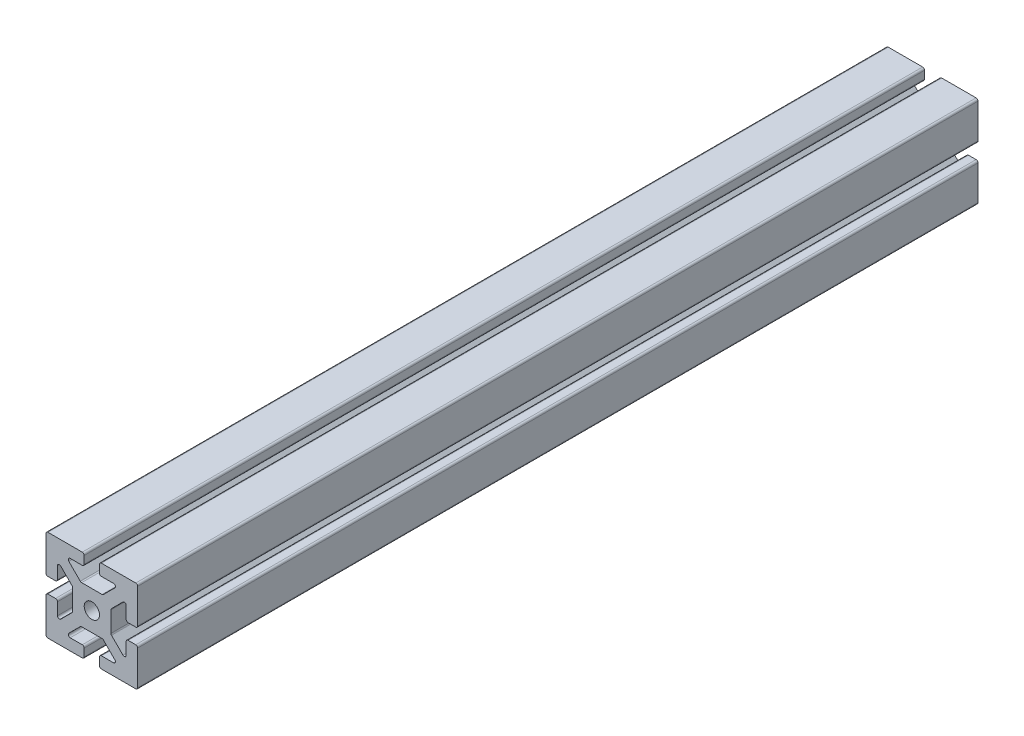
SolidWorks part; units mm, degrees
material "6061-T4 (SS)"
ref_plane "Front Plane" through (0, 0, 0) normal (0, 0, 1) x (1, 0, 0)
ref_plane "Top Plane" through (0, 0, 0) normal (0, 1, 0) x (1, 0, 0)
ref_plane "Right Plane" through (0, 0, 0) normal (1, 0, 0) x (0, 0, -1)
sketch "Sketch1" plane through (0, 0, 0) normal (0, 0, 1) x (1, 0, 0)
  line L0 (0, 0) -> (0, 6) construction
  line L5 (6, 6) -> (-6, 6) construction
  line L6 (6, 6) -> (6, -5.75) construction
  line L43 (5.75, -6) -> (-6, -6) construction
  line L45 (-6, 6) -> (-6, -6) construction
  line L49 (-1.3358, 2.5) -> (1.3358, 2.5)
  line L53 (1.5126, 2.5732) -> (3.0126, 4.0732)
  line L54 (2.8358, 4.5) -> (1.25, 4.5)
  line L55 (1, 4.75) -> (1, 5.75)
  line L56 (1.25, 6) -> (5.75, 6)
  line L60 (-1.5126, 2.5732) -> (-3.0126, 4.0732)
  line L61 (-2.8358, 4.5) -> (-1.25, 4.5)
  line L62 (-1, 4.75) -> (-1, 5.75)
  line L63 (-1.25, 6) -> (-5.75, 6)
  line L64 (6, 1.25) -> (6, 5.75)
  line L65 (4.75, 1) -> (5.75, 1)
  line L66 (4.5, 2.8358) -> (4.5, 1.25)
  line L68 (2.5732, 1.5126) -> (4.0732, 3.0126)
  line L86 (2.5, 1.3358) -> (2.5, -1.3358)
  line L87 (2.5732, -1.5126) -> (4.0732, -3.0126)
  line L88 (4.5, -2.8358) -> (4.5, -1.25)
  line L89 (4.75, -1) -> (5.75, -1)
  line L90 (6, -1.25) -> (6, -5.75)
  line L91 (1.25, -6) -> (5.75, -6)
  line L92 (1, -4.75) -> (1, -5.75)
  line L93 (2.8358, -4.5) -> (1.25, -4.5)
  line L94 (1.5126, -2.5732) -> (3.0126, -4.0732)
  line L95 (1.3358, -2.5) -> (-1.3358, -2.5)
  line L96 (-1.5126, -2.5732) -> (-3.0126, -4.0732)
  line L97 (-2.8358, -4.5) -> (-1.25, -4.5)
  line L98 (-1, -4.75) -> (-1, -5.75)
  line L99 (-1.25, -6) -> (-5.75, -6)
  line L100 (-6, -1.25) -> (-6, -5.75)
  line L101 (-4.75, -1) -> (-5.75, -1)
  line L102 (-4.5, -2.8358) -> (-4.5, -1.25)
  line L103 (-2.5732, -1.5126) -> (-4.0732, -3.0126)
  line L104 (-2.5, -1.3358) -> (-2.5, 1.3358)
  line L105 (-2.5732, 1.5126) -> (-4.0732, 3.0126)
  line L106 (-4.5, 2.8358) -> (-4.5, 1.25)
  line L107 (-4.75, 1) -> (-5.75, 1)
  line L108 (-6, 1.25) -> (-6, 5.75)
  circle A42 centre (0, 0) radius 1
  arc A43 (1, 5.75) -> (1.25, 6) centre (1.25, 5.75) cw
  arc A44 (1.25, 4.5) -> (1, 4.75) centre (1.25, 4.75) cw
  arc A45 (3.0126, 4.0732) -> (2.8358, 4.5) centre (2.8358, 4.25) ccw
  arc A46 (1.3358, 2.5) -> (1.5126, 2.5732) centre (1.3358, 2.75) ccw
  arc A47 (-1.3358, 2.5) -> (-1.5126, 2.5732) centre (-1.3358, 2.75) cw
  arc A48 (-3.0126, 4.0732) -> (-2.8358, 4.5) centre (-2.8358, 4.25) cw
  arc A49 (-1.25, 4.5) -> (-1, 4.75) centre (-1.25, 4.75) ccw
  arc A50 (-1, 5.75) -> (-1.25, 6) centre (-1.25, 5.75) ccw
  arc A51 (5.75, 1) -> (6, 1.25) centre (5.75, 1.25) ccw
  arc A52 (4.5, 1.25) -> (4.75, 1) centre (4.75, 1.25) ccw
  arc A53 (4.0732, 3.0126) -> (4.5, 2.8358) centre (4.25, 2.8358) cw
  arc A54 (2.5, 1.3358) -> (2.5732, 1.5126) centre (2.75, 1.3358) cw
  arc A55 (2.5, -1.3358) -> (2.5732, -1.5126) centre (2.75, -1.3358) ccw
  arc A56 (4.0732, -3.0126) -> (4.5, -2.8358) centre (4.25, -2.8358) ccw
  arc A57 (4.5, -1.25) -> (4.75, -1) centre (4.75, -1.25) cw
  arc A58 (5.75, -1) -> (6, -1.25) centre (5.75, -1.25) cw
  arc A59 (1, -5.75) -> (1.25, -6) centre (1.25, -5.75) ccw
  arc A60 (1.25, -4.5) -> (1, -4.75) centre (1.25, -4.75) ccw
  arc A61 (3.0126, -4.0732) -> (2.8358, -4.5) centre (2.8358, -4.25) cw
  arc A62 (1.3358, -2.5) -> (1.5126, -2.5732) centre (1.3358, -2.75) cw
  arc A63 (-1.3358, -2.5) -> (-1.5126, -2.5732) centre (-1.3358, -2.75) ccw
  arc A64 (-3.0126, -4.0732) -> (-2.8358, -4.5) centre (-2.8358, -4.25) ccw
  arc A65 (-1.25, -4.5) -> (-1, -4.75) centre (-1.25, -4.75) cw
  arc A66 (-1, -5.75) -> (-1.25, -6) centre (-1.25, -5.75) cw
  arc A67 (-5.75, -1) -> (-6, -1.25) centre (-5.75, -1.25) ccw
  arc A68 (-4.5, -1.25) -> (-4.75, -1) centre (-4.75, -1.25) ccw
  arc A69 (-4.0732, -3.0126) -> (-4.5, -2.8358) centre (-4.25, -2.8358) cw
  arc A70 (-2.5, -1.3358) -> (-2.5732, -1.5126) centre (-2.75, -1.3358) cw
  arc A71 (-2.5, 1.3358) -> (-2.5732, 1.5126) centre (-2.75, 1.3358) ccw
  arc A72 (-4.0732, 3.0126) -> (-4.5, 2.8358) centre (-4.25, 2.8358) ccw
  arc A73 (-4.5, 1.25) -> (-4.75, 1) centre (-4.75, 1.25) cw
  arc A74 (-5.75, 1) -> (-6, 1.25) centre (-5.75, 1.25) cw
  arc A75 (6, 5.75) -> (5.75, 6) centre (5.75, 5.75) ccw
  arc A76 (6, -5.75) -> (5.75, -6) centre (5.75, -5.75) cw construction
  arc A77 (-5.75, -6) -> (-6, -5.75) centre (-5.75, -5.75) cw
  arc A78 (-5.75, 6) -> (-6, 5.75) centre (-5.75, 5.75) ccw
  arc A79 (6, -5.75) -> (5.75, -6) centre (5.75, -5.75) cw
  point P0 (0, 0)
  point P16 (1, 6)
  point P24 (0, 2.5)
  point P116 (0, 0)
  dimension "D7" = 0.25
  dimension "D10" = 0.25
  dimension "D6" = 4
extrude "Boss-Extrude1" add sketch "Sketch1" against normal blind 110
equation "\"B\"= 2"
equation "\"A\"= 1.5"
equation "\"D1@Sketch1\"=\"B\""
equation "\"D2@Sketch1\"=\"B\""
equation "\"D3@Sketch1\"=\"A\""
equation "\"D4@Sketch1\"=\"B\""
equation "\"D5@Sketch1\"=\"B\"/2 + \"A\""
equation "\"D8@Sketch1\"=\"A\""
equation "\"C\"= 110"
equation "\"D1@Boss-Extrude1\"=\"C\""
